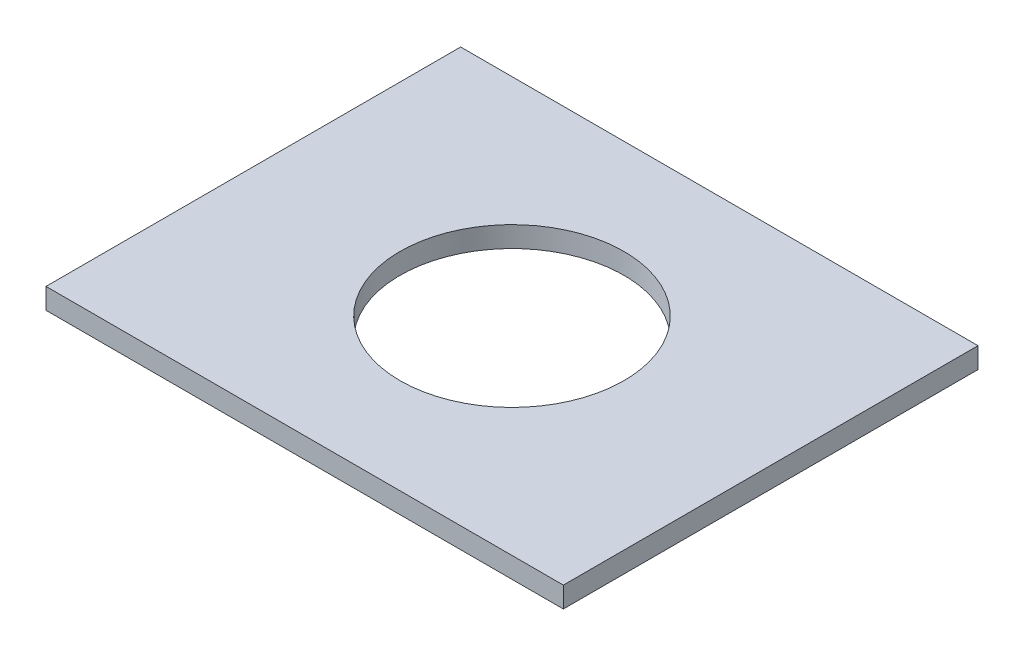
SolidWorks part; units mm, degrees
ref_plane "Front Plane" through (0, 0, 0) normal (0, 0, 1) x (1, 0, 0)
ref_plane "Top Plane" through (0, 0, 0) normal (0, 1, 0) x (1, 0, 0)
ref_plane "Right Plane" through (0, 0, 0) normal (1, 0, 0) x (0, 0, -1)
sketch "Sketch1" plane through (0, 0, 0) normal (0, 1, 0) x (1, 0, 0)
  line L0 (-62.38, -50) -> (62.38, -50)
  line L1 (-62.38, -50) -> (-62.38, 50)
  line L2 (62.38, -50) -> (62.38, 50)
  line L3 (-62.38, 50) -> (62.38, 50)
  line L4 (-62.38, -50) -> (62.38, 50) construction
  line L5 (62.38, -50) -> (-62.38, 50) construction
  point P1 (0, 0)
  dimension "D1" = 124.76
  dimension "D2" = 100
extrude "Boss-Extrude1" add sketch "Sketch1" along normal blind 5
sketch "Sketch2" plane through (0, 5, 0) normal (0, 1, 0) x (1, 0, 0)
  circle A1 centre (0, 0) radius 27
  dimension "D1" = 54
extrude "Cut-Extrude1" cut sketch "Sketch2" against normal blind 5
